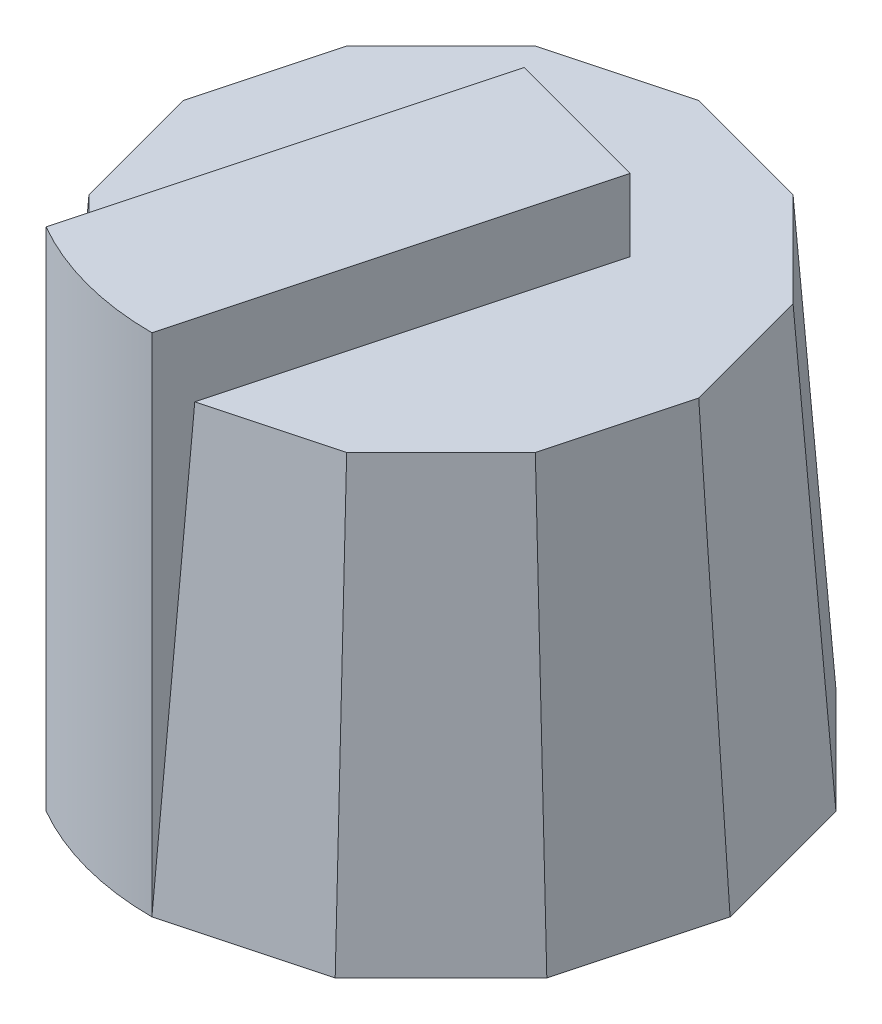
SolidWorks part; units mm, degrees
ref_plane "Front Plane" through (0, 0, 0) normal (0, 0, 1) x (1, 0, 0)
ref_plane "Top Plane" through (0, 0, 0) normal (0, 1, 0) x (1, 0, 0)
ref_plane "Right Plane" through (0, 0, 0) normal (1, 0, 0) x (0, 0, -1)
sketch "Sketch1" plane through (0, 0, 0) normal (0, 1, 0) x (1, 0, 0)
  line L0 (-20, 0) -> (-17.3205, -10)
  line L1 (20, 0) -> (17.3205, 10)
  line L2 (17.3205, 10) -> (10, 17.3205)
  line L3 (10, 17.3205) -> (0, 20)
  line L4 (0, 20) -> (-10, 17.3205)
  line L5 (-10, 17.3205) -> (-17.3205, 10)
  line L6 (-17.3205, 10) -> (-20, 0)
  line L7 (-17.3205, -10) -> (-10, -17.3205)
  line L8 (-10, -17.3205) -> (0, -20)
  line L9 (0, -20) -> (10, -17.3205)
  line L10 (10, -17.3205) -> (17.3205, -10)
  line L11 (17.3205, -10) -> (20, 0)
  circle A0 centre (0, 0) radius 19.3185 construction
  dimension "D1" = 20
extrude "Boss-Extrude1" add sketch "Sketch1" along normal blind 30 draft 4 contours L1 L2 L3 L4 L5 L6 L0 L7 L8 L9 L10 L11
sketch "Sketch3" plane through (0, 0, 0) normal (0, -1, 0) x (-1, 0, 0)
  line L0 (0, -20) -> (-10, -17.3205) construction
  line L1 (10, -17.3205) -> (0, -20)
  arc A0 (10, -17.3205) -> (0, -20) centre (0, 0) cw
extrude "Boss-Extrude2" add sketch "Sketch3" against normal blind 35 separate body
sketch "Sketch5" plane through (-5, 0, 18.6603) normal (0.2588, 0, -0.9659) x (-0.9659, 0, -0.2588)
  line L1 (5.1764, 35) -> (-5.1764, 35)
  line L2 (5.1764, 35) -> (5.1764, 0)
  line L3 (5.1764, 0) -> (-5.1764, 0)
  line L4 (-5.1764, 35) -> (-5.1764, 0)
extrude "Boss-Extrude3" add sketch "Sketch5" along normal blind 27
